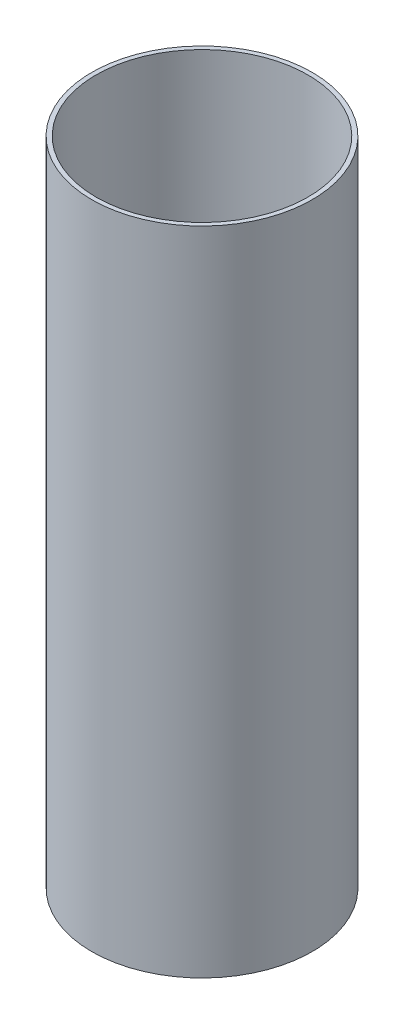
SolidWorks part; units mm, degrees
ref_plane "Front Plane" through (0, 0, 0) normal (0, 0, 1) x (1, 0, 0)
ref_plane "Top Plane" through (0, 0, 0) normal (0, 1, 0) x (1, 0, 0)
ref_plane "Right Plane" through (0, 0, 0) normal (1, 0, 0) x (0, 0, -1)
sketch "Sketch1" plane through (0, 0, 0) normal (0, 1, 0) x (1, 0, 0)
  circle A0 centre (0, 0) radius 24.4
  circle A1 centre (0, 0) radius 25.4
  dimension "D1" = 1
  dimension "D2" = 50.8
extrude "Boss-Extrude1" add sketch "Sketch1" along normal blind 150
